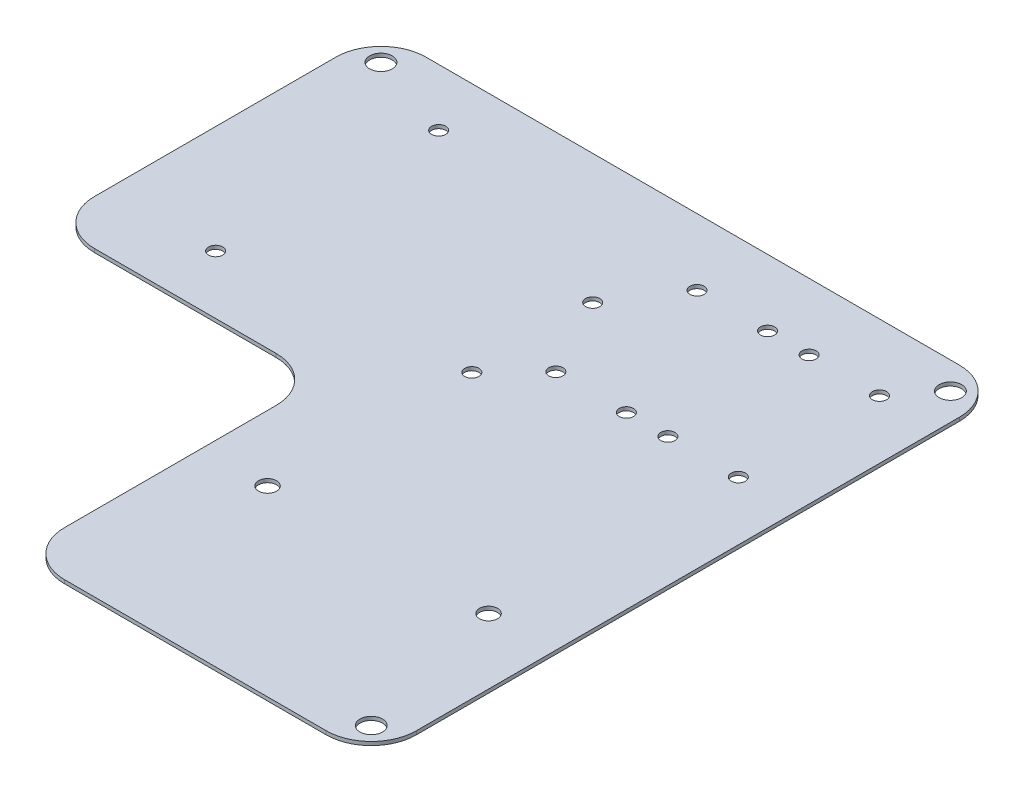
SolidWorks part; units mm, degrees
ref_plane "前视基准面" through (0, 0, 0) normal (0, 0, 1) x (1, 0, 0)
ref_plane "上视基准面" through (0, 0, 0) normal (0, 1, 0) x (1, 0, 0)
ref_plane "右视基准面" through (0, 0, 0) normal (1, 0, 0) x (0, 0, -1)
other "Configuration Table"
sketch "草图1" plane through (0, 0, 0) normal (0, 1, 0) x (1, 0, 0)
  line L1 (-51.5184, 90.4057) -> (66.7401, 90.4057)
  line L2 (-61.5184, 80.4057) -> (-61.5184, 26.9057)
  line L3 (8.7392, -49.9913) -> (35.1201, -49.9913)
  line L4 (76.7401, 80.4057) -> (76.7401, 30.1955)
  line L6 (-51.5184, 80.4057) -> (17.0816, 80.4057) construction
  line L13 (-51.5184, 80.4057) -> (-51.5184, 26.9057) construction
  line L14 (-51.5184, 26.9057) -> (17.0816, 26.9057) construction
  line L15 (17.0816, 26.9057) -> (17.0816, 80.4057) construction
  line L16 (20.2901, 80.4057) -> (41.9101, 80.4057) construction
  line L17 (20.2901, 80.4057) -> (20.2901, 27.4057) construction
  line L18 (20.2901, 27.4057) -> (41.9101, 27.4057) construction
  line L19 (41.9101, 27.4057) -> (41.9101, 80.4057) construction
  line L20 (45.1201, 80.4057) -> (45.1201, 27.4057) construction
  line L21 (45.1201, 27.4057) -> (66.7401, 27.4057) construction
  line L22 (45.1201, 80.4057) -> (66.7401, 80.4057) construction
  line L23 (66.7401, 80.4057) -> (66.7401, 27.4057) construction
  line L28 (66.7392, 21.0087) -> (8.7392, 21.0087) construction
  line L29 (66.7392, 21.0087) -> (66.7392, -39.9913) construction
  line L32 (35.1201, -49.9913) -> (66.7401, -49.9913)
  line L33 (76.7401, -39.9913) -> (76.7401, 30.1955)
  line L34 (66.7392, -39.9913) -> (8.7392, -39.9913) construction
  line L35 (8.7392, 21.0087) -> (8.7392, -39.9913) construction
  line L36 (8.7392, -9.4913) -> (66.7392, -9.4913) construction
  line L37 (37.7392, 21.0087) -> (37.7392, -39.9913) construction
  line L40 (-1.2608, -39.9913) -> (-1.2608, 6.9057)
  line L41 (-11.2608, 16.9057) -> (-51.5184, 16.9057)
  circle A0 centre (-36.0684, 77.7557) radius 1.57
  circle A1 centre (23.2901, 75.6857) radius 1.57
  circle A2 centre (38.9101, 75.6857) radius 1.57
  circle A3 centre (48.1201, 75.6857) radius 1.57
  circle A4 centre (63.7401, 75.6857) radius 1.57
  circle A5 centre (-37.6184, 29.8557) radius 1.57
  circle A6 centre (14.0816, 34.9557) radius 1.57
  circle A10 centre (14.0816, 61.7557) radius 1.57
  circle A11 centre (23.2901, 44.3857) radius 1.57
  circle A12 centre (38.9101, 44.3857) radius 1.57
  circle A13 centre (48.1201, 44.3857) radius 1.57
  circle A14 centre (63.7401, 44.3857) radius 1.57
  arc A19 (66.7401, 90.4057) -> (76.7401, 80.4057) centre (66.7401, 80.4057) cw
  arc A20 (-61.5184, 80.4057) -> (-51.5184, 90.4057) centre (-51.5184, 80.4057) cw
  circle A21 centre (13.2392, -9.4913) radius 2
  circle A22 centre (62.2392, -9.4913) radius 2
  arc A23 (66.7401, -49.9913) -> (76.7401, -39.9913) centre (66.7401, -39.9913) ccw
  arc A24 (-51.5184, 16.9057) -> (-61.5184, 26.9057) centre (-51.5184, 26.9057) cw
  arc A25 (8.7392, -49.9913) -> (-1.2608, -39.9913) centre (8.7392, -39.9913) cw
  arc A26 (-1.2608, 6.9057) -> (-11.2608, 16.9057) centre (-11.2608, 6.9057) ccw
  circle A27 centre (-55.5184, 84.4057) radius 2.5
  circle A28 centre (70.7401, 84.4057) radius 2.5
  circle A29 centre (70.7401, -43.9913) radius 2.5
  dimension "D14" = 36.02
  dimension "D15" = 3
  dimension "D19" = 24.5
  dimension "D17" = 10
  dimension "D20" = 24.5
  dimension "D25" = 10
  dimension "D28" = 6
  dimension "D30" = 6
  dimension "D32" = 6
  dimension "D2" = 3
  dimension "D3" = 8.05
  dimension "D4" = 18.65
  dimension "D5" = 3
  dimension "D6" = 13.9
  dimension "D7" = 2.95
  dimension "D8" = 2.65
  dimension "D9" = 15.45
  dimension "D10" = 15.62
  dimension "D11" = 15.62
  dimension "D12" = 4.72
  dimension "D13" = 3
  dimension "D16" = 3.2085
  dimension "D18" = 4.72
  dimension "D21" = 10
  dimension "D22" = 10
  dimension "D23" = 10
  dimension "D24" = 10
  dimension "D26" = 138.2585
  dimension "D27" = 140.397
  dimension "D29" = 6
  dimension "D31" = 6
  dimension "D33" = 6
extrude "凸台-拉伸1" add sketch "草图1" along normal blind 0.8
